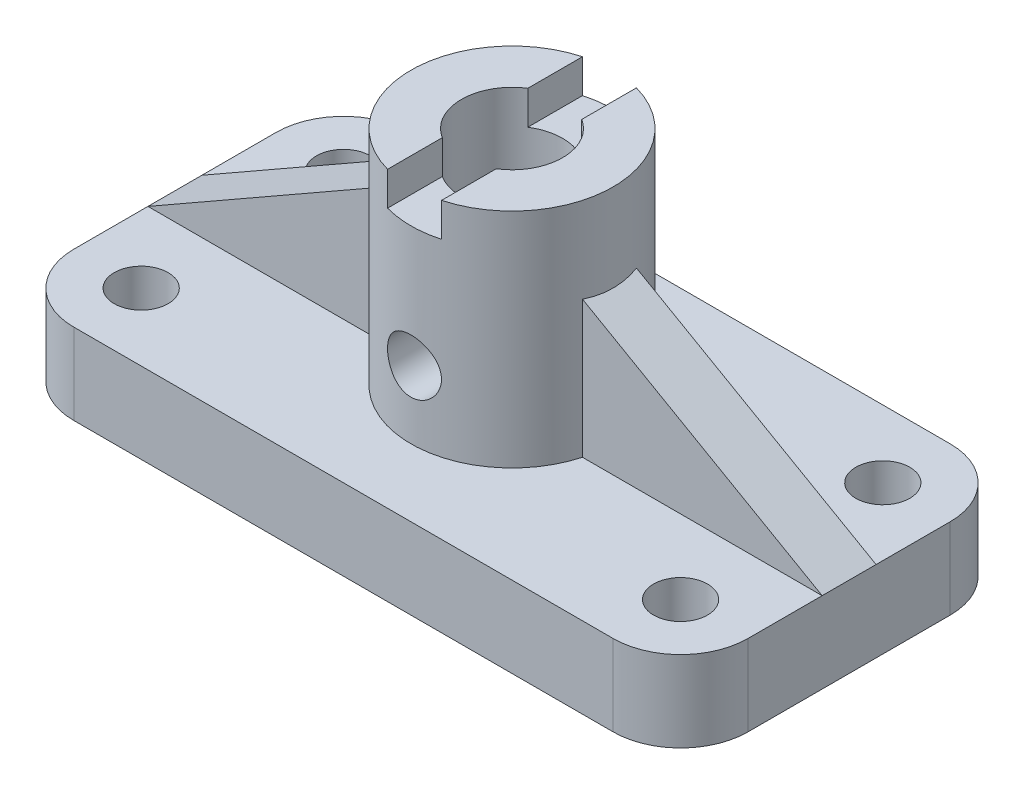
SolidWorks part; units mm, degrees
ref_plane "前视基准面" through (0, 0, 0) normal (0, 0, 1) x (1, 0, 0)
ref_plane "上视基准面" through (0, 0, 0) normal (0, 1, 0) x (1, 0, 0)
ref_plane "右视基准面" through (0, 0, 0) normal (1, 0, 0) x (0, 0, -1)
other "Configuration Table"
sketch "草图1" plane through (0, 0, 0) normal (0, 1, 0) x (1, 0, 0)
  line L1 (-40, -25) -> (40, -25)
  line L2 (-50, -15) -> (-50, 15)
  line L3 (-40, 25) -> (40, 25)
  line L4 (50, -15) -> (50, 15)
  arc A0 (-50, 15) -> (-40, 25) centre (-40, 15) cw
  arc A1 (40, -25) -> (50, -15) centre (40, -15) ccw
  arc A2 (-40, -25) -> (-50, -15) centre (-40, -15) cw
  arc A3 (40, 25) -> (50, 15) centre (40, 15) cw
  circle A4 centre (-40, 15) radius 4
  circle A5 centre (-40, -15) radius 4
  circle A6 centre (40, -15) radius 4
  circle A7 centre (40, 15) radius 4
  point P0 (0, 0)
  point P9 (-50, 25)
  point P14 (-50, -25)
  point P17 (50, 25)
  point P21 (0, 0)
  dimension "D3" = 10
  dimension "D4" = 10
  dimension "D5" = 8
  dimension "D1" = 100
  dimension "D2" = 50
extrude "凸台-拉伸1" add sketch "草图1" along normal blind 12
sketch "草图2" plane through (0, 12, 0) normal (0, 1, 0) x (1, 0, 0)
  circle A0 centre (0, 0) radius 15
  circle A1 centre (0, 0) radius 7.5
extrude "凸台-拉伸2" add sketch "草图2" along normal blind 33
sketch "草图4" plane through (0, 12, 0) normal (0, 1, 0) x (1, 0, 0)
  circle A0 centre (0, 0) radius 7.5
extrude "切除-拉伸1" cut sketch "草图4" against normal through all and the other way through all
sketch "草图5" plane through (0, 0, 0) normal (0, 0, 1) x (1, 0, 0)
  line L0 (-50, 12) -> (-15, 32)
  line L1 (-15, 45) -> (-15, 12) construction
  line L2 (-40, 12) -> (40, 12) construction
  dimension "D1" = 20
rib "筋1" sketch "草图5" sketch "草图5" thickness 8 extrusion direction parallel to sketch draft on no parameters "D1"=8
sketch "草图6" plane through (0, 0, 4) normal (0, 0, 1) x (1, 0, 0)
  line L0 (0, 45) -> (0, 0) construction
  line L1 (15, 45) -> (-15, 45) construction
mirror "镜向1" about plane through (0, 0, 0) normal (1, 0, 0) of "筋1"
sketch "草图8" plane through (0, 0, 0) normal (0, 0, 1) x (1, 0, 0)
  line L0 (0, 45) -> (0, 0) construction
  line L1 (7.5, 45) -> (-7.5, 45) construction
  line L2 (4, 40) -> (-4, 40)
  line L3 (4, 40) -> (4, 45)
  line L4 (4, 45) -> (-4, 45)
  line L5 (-4, 40) -> (-4, 45)
  line L6 (4, 40) -> (-4, 45) construction
  line L7 (4, 45) -> (-4, 40) construction
  point P2 (0, 42.5)
  dimension "D1" = 8
  dimension "D2" = 5
extrude "切除-拉伸2" cut sketch "草图8" against normal through all and the other way through all
sketch "草图9" plane through (0, 0, 0) normal (0, 0, 1) x (1, 0, 0)
  line L0 (0, 45) -> (0, 0) construction
  line L1 (14.4568, 12) -> (-14.4568, 12) construction
  circle A0 centre (0, 22) radius 4
  dimension "D1" = 10
extrude "切除-拉伸3" cut sketch "草图9" against normal through all and the other way through all
